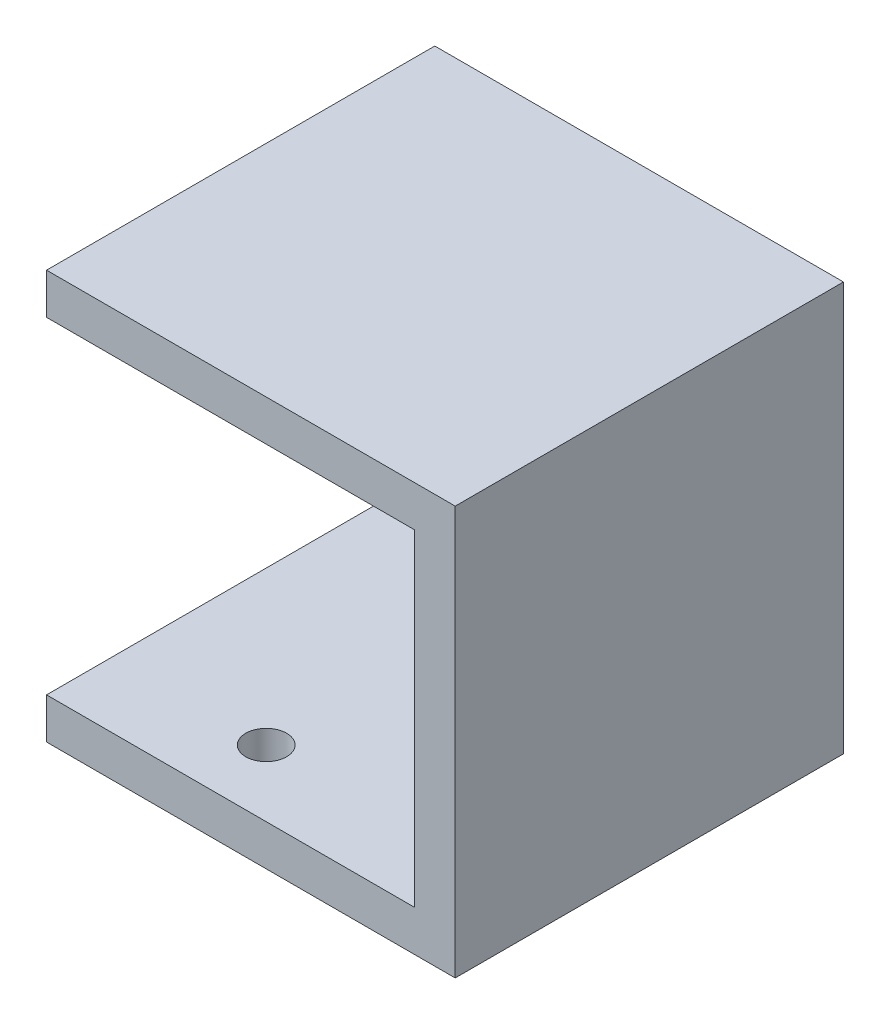
SolidWorks part; units mm, degrees
ref_plane "Plan de face" through (0, 0, 0) normal (0, 0, 1) x (1, 0, 0)
ref_plane "Plan de dessus" through (0, 0, 0) normal (0, 1, 0) x (1, 0, 0)
ref_plane "Plan de droite" through (0, 0, 0) normal (1, 0, 0) x (0, 0, -1)
sketch "Esquisse1" plane through (0, 0, 0) normal (0, 0, 1) x (1, 0, 0)
  line L0 (0, -2) -> (0, 23) construction
  line L1 (-20, -2) -> (20, -2)
  line L2 (-20, -2) -> (-20, 2)
  line L3 (-20, 2) -> (16, 2)
  line L4 (20, -2) -> (20, 2)
  line L5 (-20, 0) -> (27.2914, 0) construction
  line L6 (-20, 18) -> (81.1574, 18) construction
  line L7 (20, -2) -> (13.9809, -2)
  line L8 (20, -2) -> (20, 38)
  line L9 (20, 18) -> (16, 18)
  line L10 (16, 2) -> (16, 34)
  line L11 (-20, 38) -> (-20, 34)
  line L12 (-20, 34) -> (16, 34)
  line L13 (-20, 38) -> (20, 38)
  dimension "D1" = 4
  dimension "D2" = 40
  dimension "D3" = 4
  dimension "D4" = 20
extrude "Boss.-Extru.1" add sketch "Esquisse1" along normal blind 38 contours L13 L11 L12 L10 L9 L8 | L10 L3 L2 L1 L4 L8 L9
sketch "Esquisse2" plane through (0, -2, 0) normal (0, -1, 0) x (1, 0, 0)
  line L0 (-20, 19) -> (45.0115, 19) construction
  line L1 (-20, 38) -> (-20, 0) construction
  line L2 (-5, 31.5) -> (-5, 6.5)
  circle A0 centre (-5, 31.5) radius 2
  circle A1 centre (-5, 6.5) radius 2
  dimension "D1" = 4
  dimension "D2" = 25
  dimension "D3" = 15
extrude "Enlèv. mat.-Extru.1" cut sketch "Esquisse2" against normal blind 10
